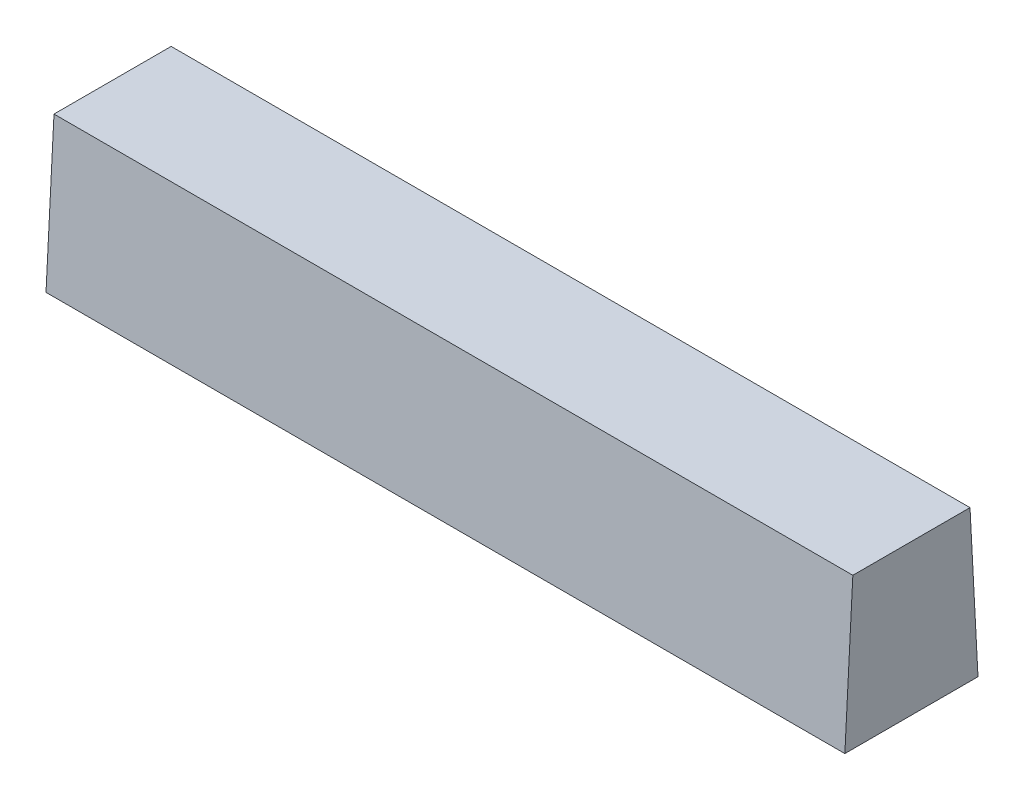
SolidWorks part; units mm, degrees
ref_plane "Front Plane" through (0, 0, 0) normal (0, 0, 1) x (1, 0, 0)
ref_plane "Top Plane" through (0, 0, 0) normal (0, 1, 0) x (1, 0, 0)
ref_plane "Right Plane" through (0, 0, 0) normal (1, 0, 0) x (0, 0, -1)
sketch "Sketch2" plane through (0, 0, 0) normal (1, 0, 0) x (0, 0, -1)
  line L0 (0, 0) -> (0, 1.13) construction
  line L1 (-0.44, 1.13) -> (0.44, 1.13)
  line L2 (0.44, 1.13) -> (0.5, 0)
  line L3 (0.5, 0) -> (-0.5, 0)
  line L4 (-0.44, 1.13) -> (-0.5, 0)
  dimension "D1" = 0.5
  dimension "D2" = 1.13
  dimension "D3" = 0.44
extrude "Boss-Extrude1" add sketch "Sketch2" along normal blind 6
